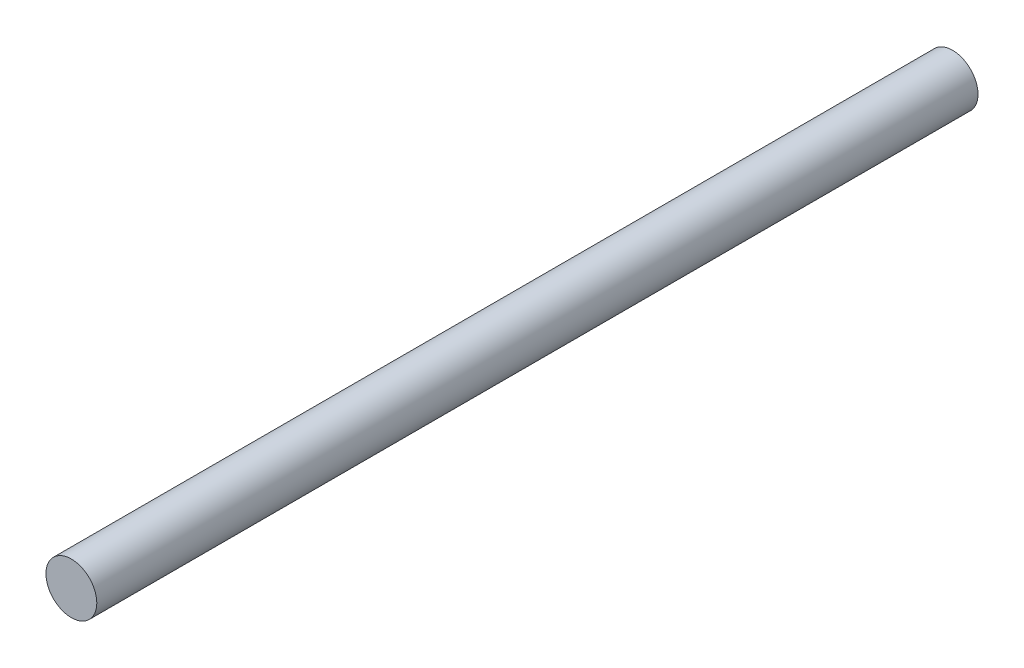
SolidWorks part; units mm, degrees
ref_plane "Front Plane" through (0, 0, 0) normal (0, 0, 1) x (1, 0, 0)
ref_plane "Top Plane" through (0, 0, 0) normal (0, 1, 0) x (1, 0, 0)
ref_plane "Right Plane" through (0, 0, 0) normal (1, 0, 0) x (0, 0, -1)
sketch "Sketch1" plane through (0, 0, 0) normal (0, 0, 1) x (1, 0, 0)
  circle A0 centre (0, 0) radius 2.3813
  dimension "D1" = 4.7625
extrude "Boss-Extrude1" add sketch "Sketch1" along normal blind 82.55
